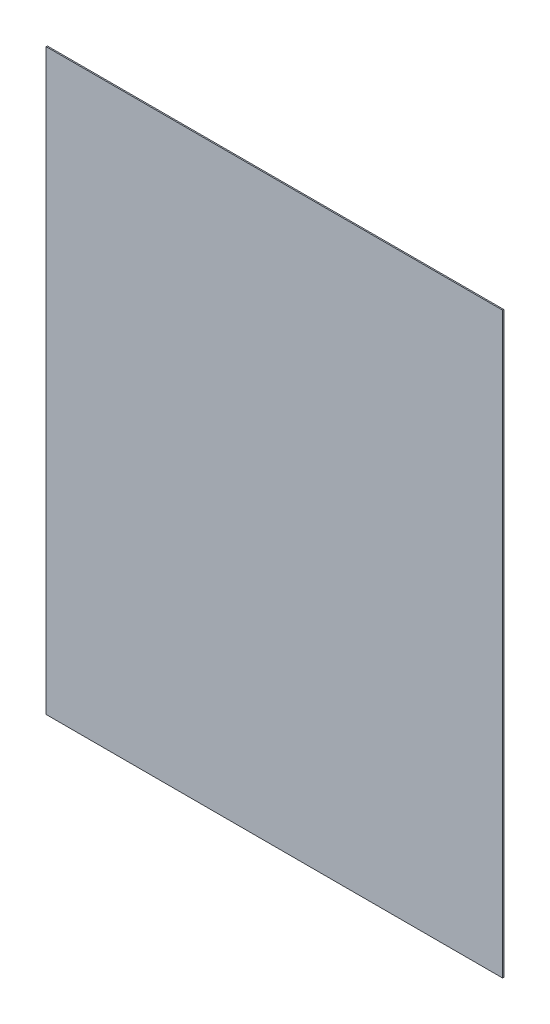
SolidWorks part; units mm, degrees
ref_plane "Alzado" through (0, 0, 0) normal (0, 0, 1) x (1, 0, 0)
ref_plane "Planta" through (0, 0, 0) normal (0, 1, 0) x (1, 0, 0)
ref_plane "Vista lateral" through (0, 0, 0) normal (1, 0, 0) x (0, 0, -1)
sketch "Croquis1" plane through (0, 0, 0) normal (0, 0, 1) x (1, 0, 0)
  line L1 (-355, 450) -> (355, 450)
  line L2 (-355, 450) -> (-355, -450)
  line L3 (-355, -450) -> (355, -450)
  line L4 (355, 450) -> (355, -450)
  line L5 (-355, 450) -> (355, -450) construction
  line L6 (-355, -450) -> (355, 450) construction
  point P0 (0, 0)
  dimension "D1" = 710
  dimension "D2" = 900
extrude "Saliente-Extruir1" add sketch "Croquis1" along normal blind 1.9
